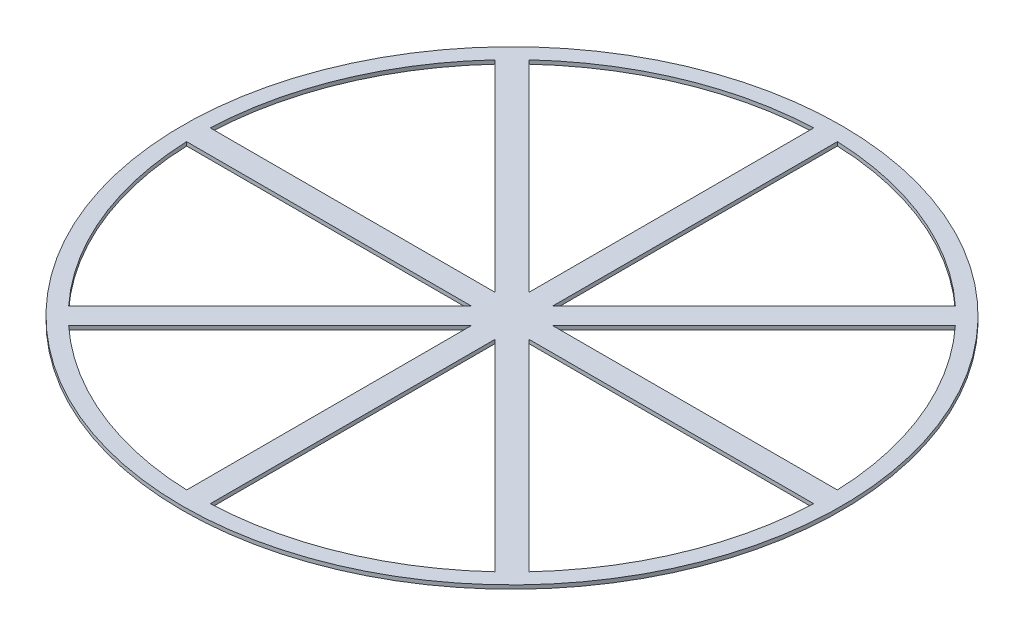
SolidWorks part; units mm, degrees
material "7050-T7651"
ref_plane "Front Plane" through (0, 0, 0) normal (0, 0, 1) x (1, 0, 0)
ref_plane "Top Plane" through (0, 0, 0) normal (0, 1, 0) x (1, 0, 0)
ref_plane "Right Plane" through (0, 0, 0) normal (1, 0, 0) x (0, 0, -1)
sketch "Sketch1" plane through (0, 0, 0) normal (0, 1, 0) x (1, 0, 0)
  line L0 (4.7625, 125.894) -> (4.7625, 11.4977)
  line L1 (-4.7625, 125.894) -> (-4.7625, 11.4977)
  line L2 (-4.7625, 101.5638) -> (4.7625, 101.5638) construction
  line L3 (85.6529, 92.3881) -> (4.7625, 11.4977)
  line L4 (68.4489, 75.1841) -> (75.1841, 68.4489) construction
  line L5 (92.3881, 85.6529) -> (11.4977, 4.7625)
  line L6 (125.894, 4.7625) -> (11.4977, 4.7625)
  line L7 (101.5638, 4.7625) -> (101.5638, -4.7625) construction
  line L8 (125.894, -4.7625) -> (11.4977, -4.7625)
  line L9 (92.3881, -85.6529) -> (11.4977, -4.7625)
  line L10 (75.1841, -68.4489) -> (68.4489, -75.1841) construction
  line L11 (85.6529, -92.3881) -> (4.7625, -11.4977)
  line L12 (4.7625, -125.894) -> (4.7625, -11.4977)
  line L13 (4.7625, -101.5638) -> (-4.7625, -101.5638) construction
  line L14 (-4.7625, -125.894) -> (-4.7625, -11.4977)
  line L15 (-85.6529, -92.3881) -> (-4.7625, -11.4977)
  line L16 (-68.4489, -75.1841) -> (-75.1841, -68.4489) construction
  line L17 (-92.3881, -85.6529) -> (-11.4977, -4.7625)
  line L18 (-125.894, -4.7625) -> (-11.4977, -4.7625)
  line L19 (-101.5638, -4.7625) -> (-101.5638, 4.7625) construction
  line L20 (-125.894, 4.7625) -> (-11.4977, 4.7625)
  line L21 (-92.3881, 85.6529) -> (-11.4977, 4.7625)
  line L22 (-75.1841, 68.4489) -> (-68.4489, 75.1841) construction
  line L23 (-85.6529, 92.3881) -> (-4.7625, 11.4977)
  line L25 (-4.7625, 11.4977) -> (-4.7625, 18.0455)
  line L26 (-11.4977, 4.7625) -> (-17.9605, 4.7625)
  line L28 (-11.4977, -4.7625) -> (-16.0676, -9.3324)
  line L33 (-4.7625, 11.4977) -> (-9.3925, 16.1277)
  line L35 (4.7625, 11.4977) -> (6.6224, 13.3576)
  line L37 (4.7625, 11.4977) -> (4.7625, 18.0455)
  line L39 (11.4977, 4.7625) -> (14.1279, 4.7625)
  line L41 (11.4977, 4.7625) -> (16.1277, 9.3925)
  line L43 (11.4977, -4.7625) -> (13.3576, -6.6224)
  line L45 (11.4977, -4.7625) -> (18.0455, -4.7625)
  line L46 (4.7625, -11.4977) -> (4.7625, -14.1279)
  line L49 (4.7625, -11.4977) -> (9.3925, -16.1277)
  line L50 (-4.7625, -11.4977) -> (-6.6224, -13.3576)
  line L52 (-4.7625, -11.4977) -> (-4.7625, -14.1279)
  line L55 (-11.4977, -4.7625) -> (-14.1279, -4.7625)
  line L57 (-11.4977, 4.7625) -> (-13.3576, 6.6224)
  circle A0 centre (0, 0) radius 132.334
  arc A2 (-4.7625, 125.894) -> (-85.6529, 92.3881) centre (0, 0) ccw
  arc A3 (85.6529, 92.3881) -> (4.7625, 125.894) centre (0, 0) ccw
  arc A4 (125.894, 4.7625) -> (92.3881, 85.6529) centre (0, 0) ccw
  arc A5 (92.3881, -85.6529) -> (125.894, -4.7625) centre (0, 0) ccw
  arc A6 (4.7625, -125.894) -> (85.6529, -92.3881) centre (0, 0) ccw
  arc A7 (-85.6529, -92.3881) -> (-4.7625, -125.894) centre (0, 0) ccw
  arc A8 (-125.894, -4.7625) -> (-92.3881, -85.6529) centre (0, 0) ccw
  arc A9 (-92.3881, 85.6529) -> (-125.894, 4.7625) centre (0, 0) ccw
  point P11 (0, 101.5638)
  point P56 (0, 0)
  dimension "D1" = 264.668
  dimension "D3" = 6.35
  dimension "D4" = 9.525
extrude "Boss-Extrude1" add sketch "Sketch1" along normal blind 1.524 contours A0 A9 L21 L20 A8 L18 L17 A7 L15 L14 A6 L12 L11 A5 L9 L8 A4 L6 L5 A3 L3 L0 A2 L1 L23
